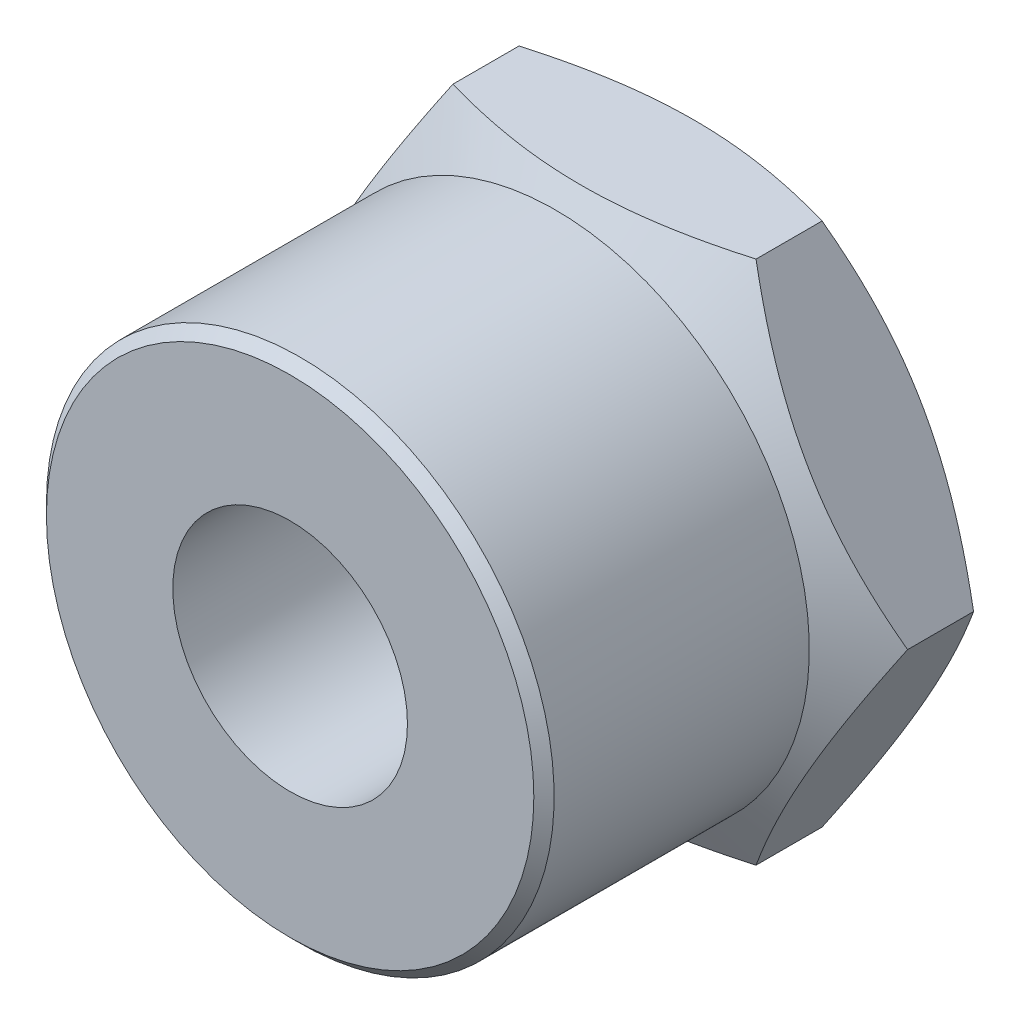
SolidWorks part; units mm, degrees
ref_plane "Front" through (0, 0, 0) normal (0, 0, 1) x (1, 0, 0)
ref_plane "Top" through (0, 0, 0) normal (0, 1, 0) x (1, 0, 0)
ref_plane "Right" through (0, 0, 0) normal (1, 0, 0) x (0, 0, -1)
sketch "Sketch1" plane through (0, 0, 0) normal (0, 0, 1) x (1, 0, 0)
  line L1 (1.5877, -2.75) -> (3.1754, 0)
  line L2 (3.1754, 0) -> (1.5877, 2.75)
  line L3 (1.5877, 2.75) -> (-1.5877, 2.75)
  line L4 (-1.5877, 2.75) -> (-3.1754, 0)
  line L5 (-3.1754, 0) -> (-1.5877, -2.75)
  line L6 (-1.5877, -2.75) -> (1.5877, -2.75)
  circle A0 centre (0, 0) radius 2.75 construction
  circle A1 centre (0, 0) radius 1.2295
  dimension "xd" = 2.459
  dimension "s" = 5.5
extrude "BaseNut" add sketch "Sketch1" against normal blind 1.72
cosmetic thread "ThreadCosmetic1" [suppressed] parameters "m"=2.15, "D2"=3
sketch "Sketch3" plane through (0, 0, 0) normal (0, 1, 0) x (1, 0, 0)
  line L0 (0, 16.3108) -> (0, -16.1137) construction
  line L2 (-2.0696, 0.86) -> (33.5085, 0.86) construction
  line L3 (2.285, 1.72) -> (3.1754, 1.72)
  line L5 (3.1754, 1.72) -> (3.1754, 1.2059)
  line L7 (3.1754, 1.2059) -> (2.285, 1.72)
  line L8 (3.1754, 0.5141) -> (2.285, 0)
  line L9 (3.1754, 0) -> (3.1754, 0.5141)
  line L10 (2.285, 0) -> (3.1754, 0)
  dimension "D1" = 30
  dimension "dw" = 4.57
revolve "Double-Chamfer" cut sketch "Sketch3" angle 360 about L0
sketch "Sketch2" plane through (20.0871, -4.2815, 0) normal (0, 0, 1) x (1, 0, 0)
  circle A1 centre (-20.0871, 4.2815) radius 1.2295 construction
  circle A2 centre (-20.0871, 4.2815) radius 2.66
  circle A3 centre (-20.0871, 4.2815) radius 1.2295
  dimension "s1" = 5.32
extrude "Extrude1" add sketch "Sketch2" along normal offset from surface (2.78 mm away) 4.5 up to face at (1.2295, 0, -1.72)
sketch "Sketch5" plane through (0, 0, 0) normal (0, 1, 0) x (1, 0, 0)
  line L0 (0, 16.8008) -> (0, -2.8116) construction
  line L2 (1.2295, 1.72) -> (1.725, 1.72)
  line L5 (1.725, 1.72) -> (1.2295, 1.2245)
  line L7 (1.2295, 1.2245) -> (1.2295, 1.72)
  dimension "D1" = 45
  dimension "da" = 3.45
revolve "EndChamfer" cut sketch "Sketch5" angle 360 about L0
chamfer "Chamfer1" distance 0.1064 angle 45 1 edges at (2.66, 0, 2.78)
sketch "Sketch6" plane through (0, 0, 0) normal (0, 1, 0) x (1, 0, 0)
  line L0 (0, 30.0005) -> (0, -32.7386) construction
  line L1 (0.959, 1.3598) -> (1.2295, 1.3598)
  line L2 (1.2295, 1.3598) -> (1.4638, 1.2245)
  line L3 (1.4638, 1.2245) -> (1.2295, 1.0893)
  line L4 (1.2295, 1.0893) -> (0.959, 1.0893)
  line L5 (0.959, 1.0893) -> (0.959, 1.3598)
  line L6 (-1.2295, 1.2245) -> (1.2295, 1.2245) construction
  dimension "D1" = 0.2705
  dimension "D2" = 2.459
revolve "Cut-Revolve10" [suppressed] cut sketch "Sketch6" angle 360 about L0
pattern_linear "LPattern10" [suppressed] count 5 spacing 0.3246 along (0, 0, 1)
equation "\"D1@Chamfer1\" = \"s1@Sketch2\" / 50"
equation "\"D2@Sketch6\" = \"xd@Sketch1\""
equation "\"D1@Sketch6\" = (  \"D2@ThreadCosmetic1\" - \"xd@Sketch1\" )  / 2"
equation "\"D3@LPattern10\" = \"D1@Sketch6\" * 1.2"
equation "\"D1@LPattern10\" = \"m1@BaseNut\" / \"D3@LPattern10\""
